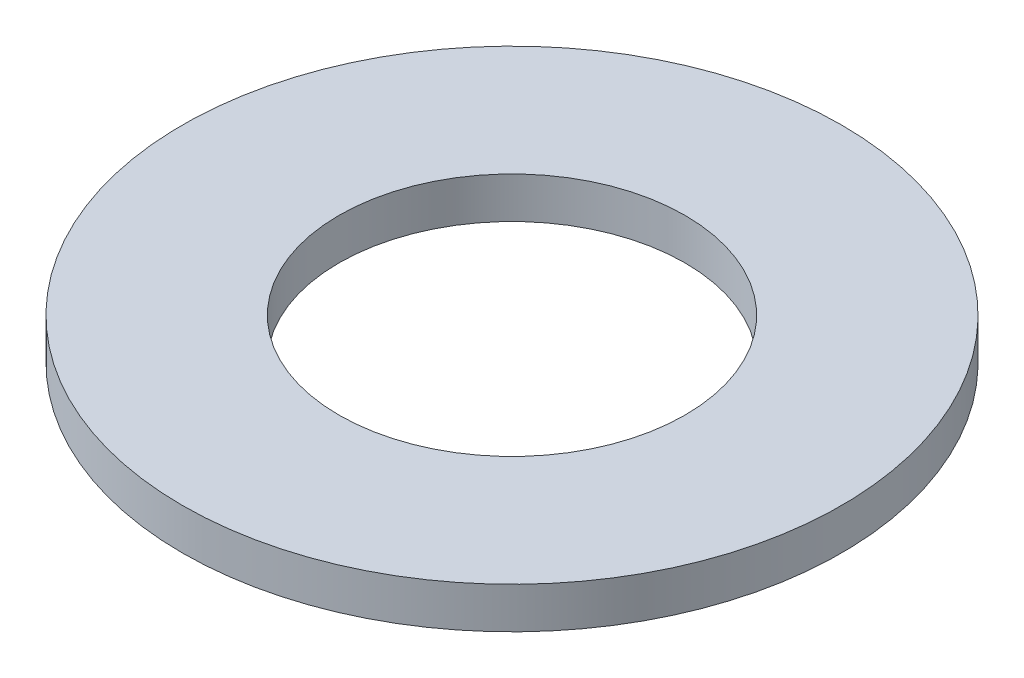
SolidWorks part; units mm, degrees
ref_plane "Front Plane" through (0, 0, 0) normal (0, 0, 1) x (1, 0, 0)
ref_plane "Top Plane" through (0, 0, 0) normal (0, 1, 0) x (1, 0, 0)
ref_plane "Right Plane" through (0, 0, 0) normal (1, 0, 0) x (0, 0, -1)
sketch "Sketch1" plane through (0, 0, 0) normal (0, 1, 0) x (1, 0, 0)
  circle A0 centre (0, 0) radius 4.2
  circle A1 centre (0, 0) radius 8
  dimension "D1" = 8.4
  dimension "D2" = 16
extrude "Boss-Extrude1" add sketch "Sketch1" along normal blind 1 contours A1 A0
